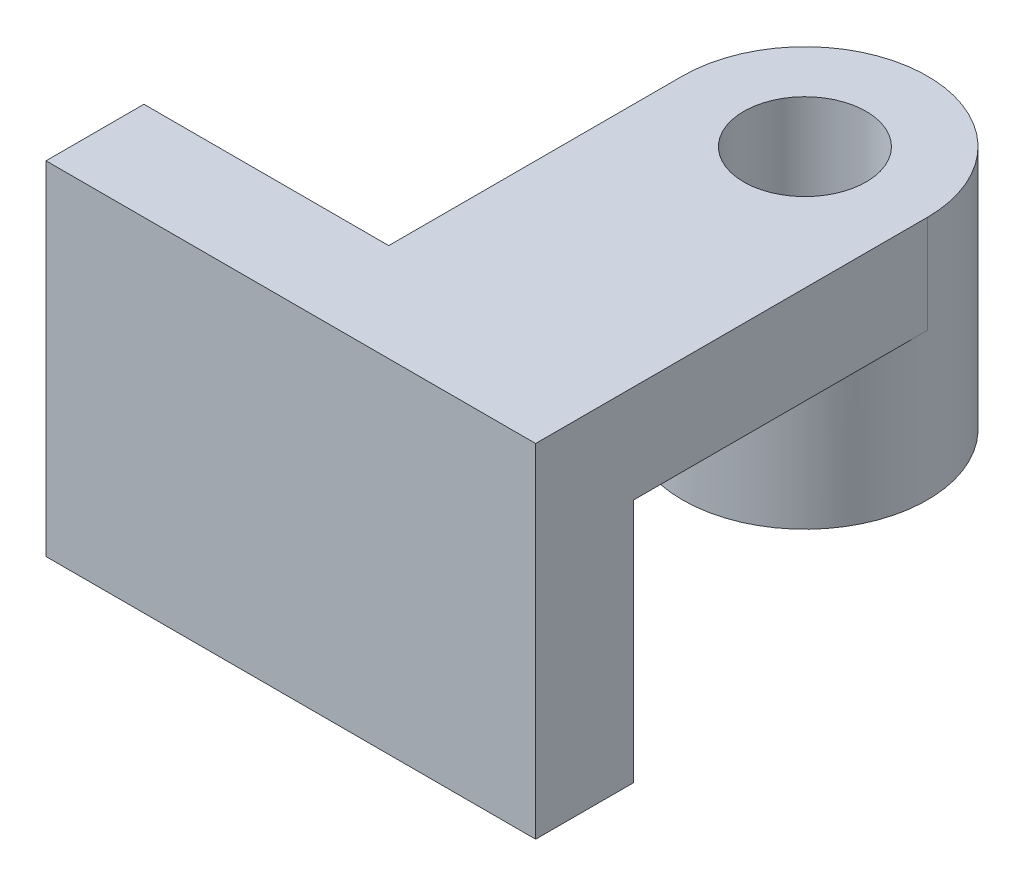
SolidWorks part; units mm, degrees
ref_plane "Plan de face" through (0, 0, 0) normal (0, 0, 1) x (1, 0, 0)
ref_plane "Plan de dessus" through (0, 0, 0) normal (0, 1, 0) x (1, 0, 0)
ref_plane "Plan de droite" through (0, 0, 0) normal (1, 0, 0) x (0, 0, -1)
sketch "ESQUISSE_BASE" plane through (0, 0, 0) normal (0, 0, 1) x (1, 0, 0)
  line L1 (-63.5, 44.45) -> (63.5, 44.45)
  line L2 (-63.5, 44.45) -> (-63.5, -44.45)
  line L3 (-63.5, -44.45) -> (63.5, -44.45)
  line L4 (63.5, 44.45) -> (63.5, -44.45)
  line L5 (-63.5, 44.45) -> (63.5, -44.45) construction
  line L6 (-63.5, -44.45) -> (63.5, 44.45) construction
  point P0 (0, 0)
  dimension "D1" = 88.9
  dimension "D2" = 127
extrude "VOLUME_BASE" add sketch "ESQUISSE_BASE" along normal blind 25.4
sketch "ESQUISSE_ARRIERE" plane through (0, 44.45, 0) normal (0, 1, 0) x (1, 0, 0)
  line L0 (63.5, -25.4) -> (63.5, 76.2)
  line L1 (63.5, 76.2) -> (0, 76.2)
  line L2 (0, 76.2) -> (0, -25.4)
  line L3 (63.5, -25.4) -> (-63.5, -25.4) construction
  line L4 (0, -25.4) -> (63.5, -25.4)
  dimension "D1" = 101.6
  dimension "D2" = 63.5
extrude "VOLUME_ARRIERE" add sketch "ESQUISSE_ARRIERE" against normal blind 25.4 contours L4 L0 L1 L2
sketch "ESQUISSE_CYLINDRE" plane through (0, 44.45, 0) normal (0, 1, 0) x (1, 0, 0)
  line L0 (63.5, 76.2) -> (0, 76.2) construction
  circle A0 centre (31.75, 76.2) radius 31.75
extrude "VOLUME_CYLINDRE" add sketch "ESQUISSE_CYLINDRE" against normal blind 63.5
sketch "Esquisse4" plane through (0, 44.45, 0) normal (0, 1, 0) x (1, 0, 0)
  line L0 (0, 76.2) -> (63.5, 76.2) construction
  circle A1 centre (31.75, 76.2) radius 15.875
  dimension "D1" = 31.75
extrude "Enlèv. mat.-Extru.1" cut sketch "Esquisse4" against normal through all contours A1
